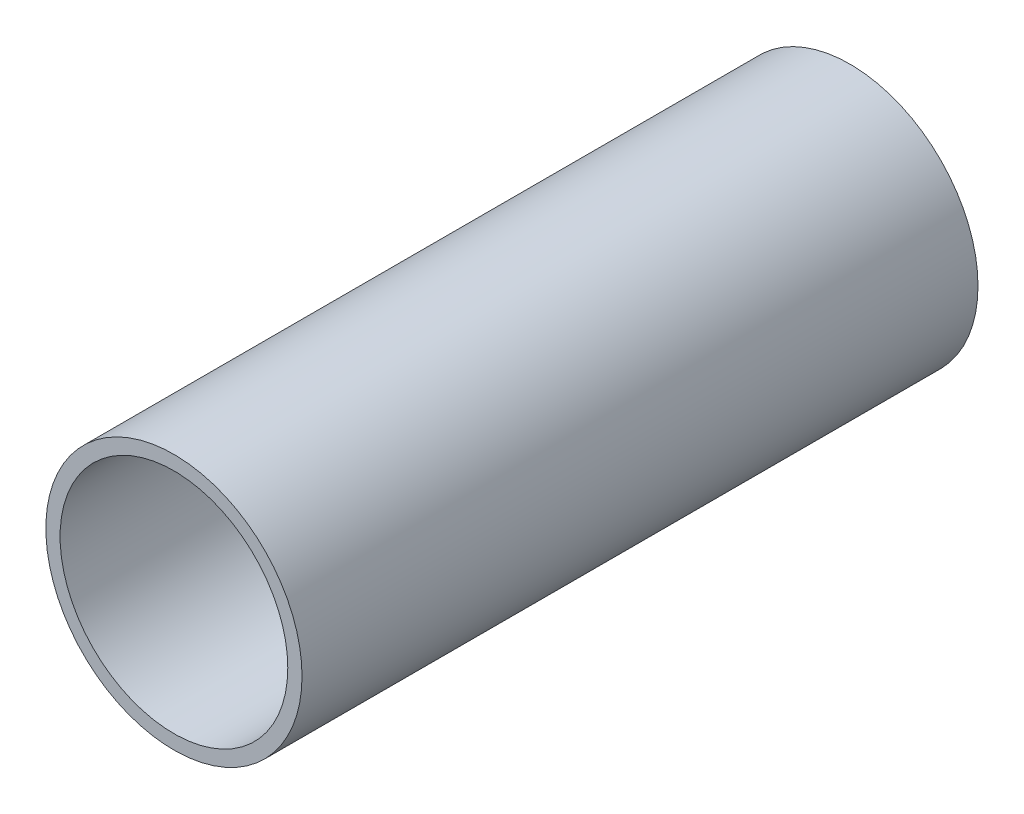
SolidWorks part; units mm, degrees
material "PVC Rigid"
ref_plane "Front Plane" through (0, 0, 0) normal (0, 0, 1) x (1, 0, 0)
ref_plane "Top Plane" through (0, 0, 0) normal (0, 1, 0) x (1, 0, 0)
ref_plane "Right Plane" through (0, 0, 0) normal (1, 0, 0) x (0, 0, -1)
sketch "Sketch1" plane through (0, 0, 0) normal (0, 0, 1) x (1, 0, 0)
  circle A0 centre (0, 0) radius 57.15
  circle A1 centre (0, 0) radius 50.8
  dimension "D1" = 114.3
  dimension "D2" = 101.6
extrude "Boss-Extrude1" add sketch "Sketch1" along normal mid plane 301.625
